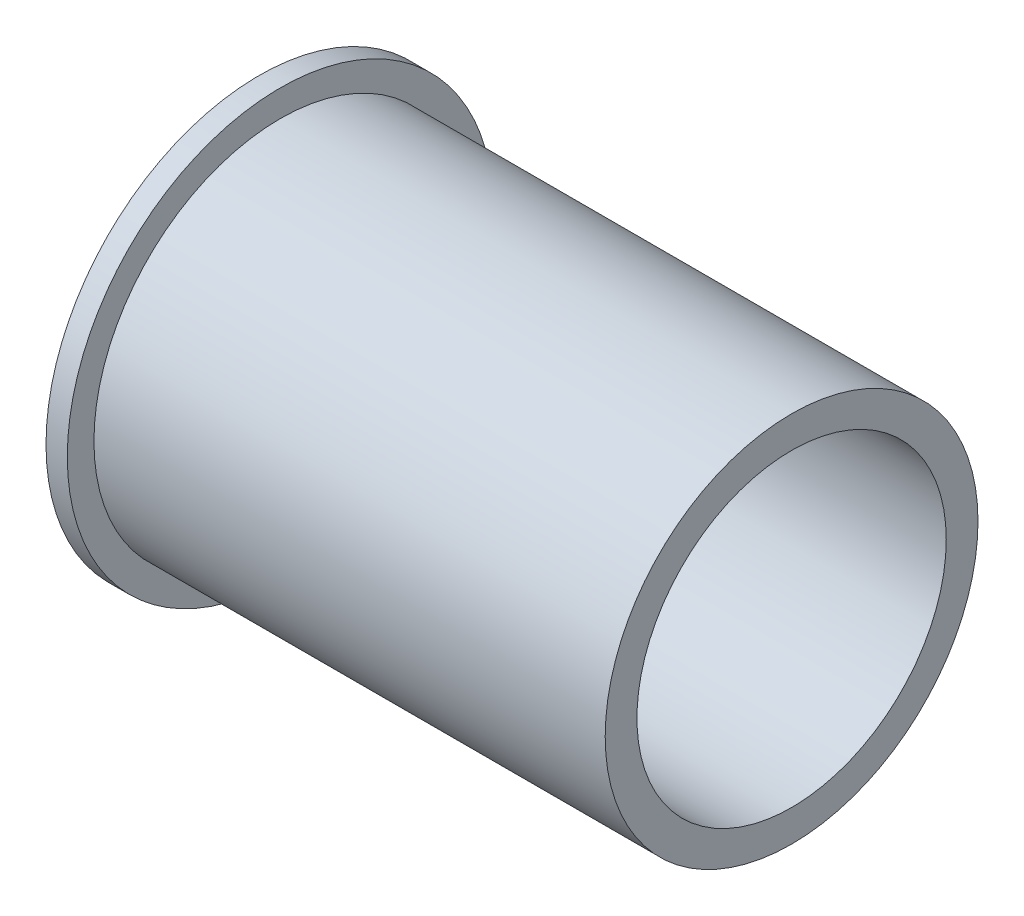
SolidWorks part; units mm, degrees
material "Tin Bearing Bronze"
ref_plane "Front Plane" through (0, 0, 0) normal (0, 0, 1) x (1, 0, 0)
ref_plane "Top Plane" through (0, 0, 0) normal (0, 1, 0) x (1, 0, 0)
ref_plane "Right Plane" through (0, 0, 0) normal (1, 0, 0) x (0, 0, -1)
sketch "Sketch1" plane through (0, 0, 0) normal (1, 0, 0) x (0, 0, -1)
  circle A0 centre (0, 0) radius 9.2202
  circle A1 centre (0, 0) radius 11.1125
  dimension "D1" = 18.4404
  dimension "D2" = 22.225
extrude "Boss-Extrude1" add sketch "Sketch1" along normal blind 31.75
sketch "Sketch2" plane through (0, 0, 0) normal (-1, 0, 0) x (0, 0, 1)
  circle A0 centre (0, 0) radius 12.7
  circle A1 centre (0, 0) radius 11.1125 construction
  circle A2 centre (0, 0) radius 11.1125
  dimension "D1" = 25.4
extrude "Boss-Extrude2" add sketch "Sketch2" against normal blind 1.27
